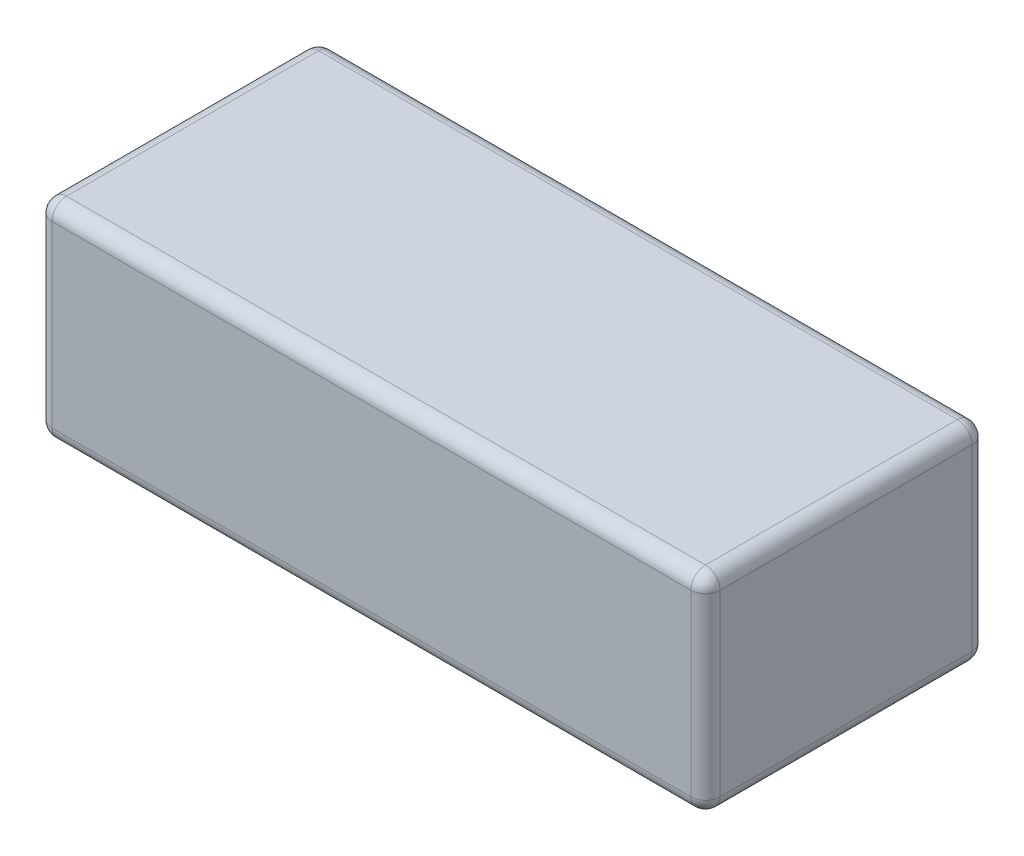
SolidWorks part; units mm, degrees
material "PTFE (general)"
ref_plane "Front Plane" through (0, 0, 0) normal (0, 0, 1) x (1, 0, 0)
ref_plane "Top Plane" through (0, 0, 0) normal (0, 1, 0) x (1, 0, 0)
ref_plane "Right Plane" through (0, 0, 0) normal (1, 0, 0) x (0, 0, -1)
sketch "Sketch1" plane through (0, 0, 0) normal (0, 1, 0) x (1, 0, 0)
  line L1 (-197.218, 62.6053) -> (-14.218, 62.6053)
  line L2 (-197.218, 62.6053) -> (-197.218, -14.3947)
  line L3 (-197.218, -14.3947) -> (-14.218, -14.3947)
  line L4 (-14.218, 62.6053) -> (-14.218, -14.3947)
  dimension "D1" = 183
  dimension "D2" = 77
extrude "Boss-Extrude1" add sketch "Sketch1" along normal blind 57
fillet "Fillet1" radius 4 12 edges at (-14.218, 28.5, 14.3947) (-197.218, 28.5, 14.3947) (-14.218, 28.5, -62.6053) (-197.218, 28.5, -62.6053) (-105.718, 0, 14.3947) (-14.218, 0, -24.1053) (-105.718, 0, -62.6053) (-197.218, 0, -24.1053) (-105.718, 57, -62.6053) (-14.218, 57, -24.1053) (-105.718, 57, 14.3947) (-197.218, 57, -24.1053)
ref_plane "Plane1" through (-105.718, 0, 0) normal (1, 0, 0) x (0, 0, -1)
sketch "Sketch2" plane through (-105.718, 0, 0) normal (1, 0, 0) x (0, 0, -1)
  circle A0 centre (25.3917, 29.254) radius 19.2599
extrude "Cut-Extrude1" cut sketch "Sketch2" along normal mid plane 84
